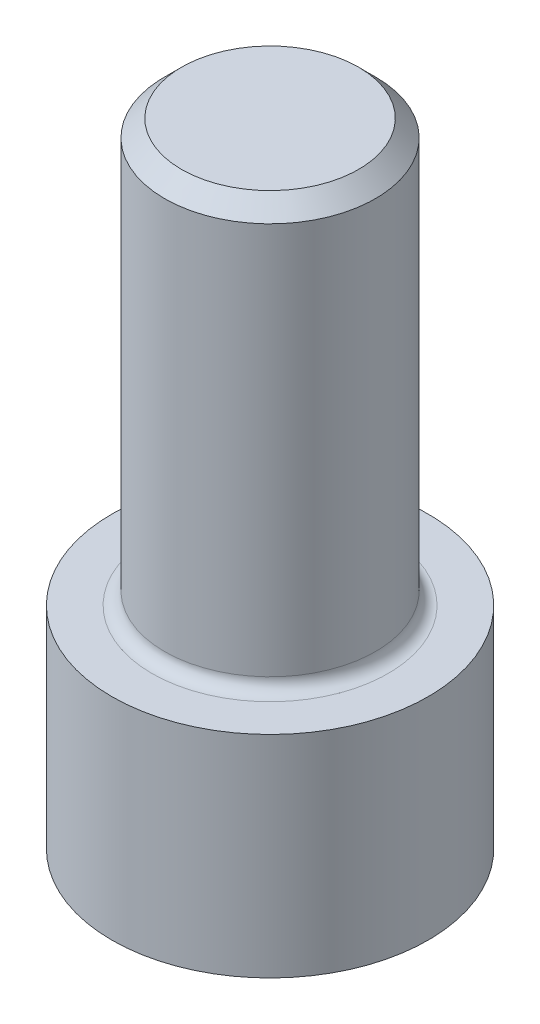
SolidWorks part; units mm, degrees
ref_plane "Front Plane" through (0, 0, 0) normal (0, 0, 1) x (1, 0, 0)
ref_plane "Top Plane" through (0, 0, 0) normal (0, 1, 0) x (1, 0, 0)
ref_plane "Right Plane" through (0, 0, 0) normal (1, 0, 0) x (0, 0, -1)
sketch "Sketch1" plane through (0, 0, 0) normal (0, 1, 0) x (1, 0, 0)
  circle A0 centre (0, 0) radius 0.1875
  dimension "D1" = 0.375
extrude "Boss-Extrude1" add sketch "Sketch1" along normal blind 0.25
sketch "Sketch2" plane through (0, 0.25, 0) normal (0, 1, 0) x (1, 0, 0)
  circle A0 centre (0, 0) radius 0.125
  dimension "D1" = 0.25
extrude "Boss-Extrude2" add sketch "Sketch2" along normal blind 0.5
fillet "Fillet1" radius 0.015 1 edges at (0, 0.25, 0.125)
chamfer "Chamfer1" distance 0.02 angle 45 1 edges at (0, 0.75, 0.125)
sketch "Sketch3" plane through (0, 0, 0) normal (0, -1, 0) x (1, 0, 0)
  line L1 (0.0875, -0.0484) -> (0.0857, 0.0516)
  line L2 (0.0857, 0.0516) -> (-0.0019, 0.1)
  line L3 (-0.0019, 0.1) -> (-0.0875, 0.0484)
  line L4 (-0.0875, 0.0484) -> (-0.0857, -0.0516)
  line L5 (-0.0857, -0.0516) -> (0.0019, -0.1)
  line L6 (0.0019, -0.1) -> (0.0875, -0.0484)
  circle A0 centre (0, 0) radius 0.0866 construction
  dimension "D1" = 0.2
extrude "Cut-Extrude1" cut sketch "Sketch3" against normal blind 0.15
